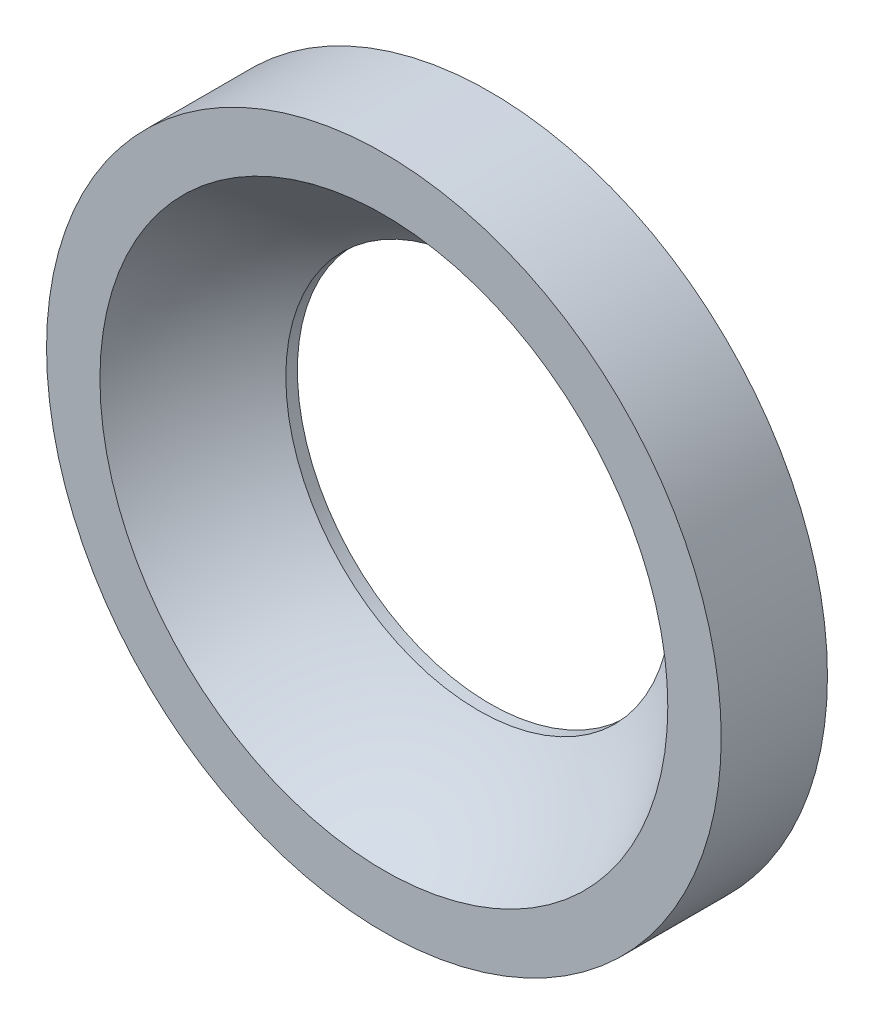
SolidWorks part; units mm, degrees
ref_plane "Front Plane" through (0, 0, 0) normal (0, 0, 1) x (1, 0, 0)
ref_plane "Top Plane" through (0, 0, 0) normal (0, 1, 0) x (1, 0, 0)
ref_plane "Right Plane" through (0, 0, 0) normal (1, 0, 0) x (0, 0, -1)
sketch "Sketch2" plane through (0, 0, 0) normal (0, 0, 1) x (1, 0, 0)
  circle A0 centre (0, 0) radius 22.225
  dimension "D1" = 44.45
extrude "Boss-Extrude1" add sketch "Sketch2" along normal blind 7
sketch "Sketch3" plane through (0, 0, 7) normal (0, 0, 1) x (1, 0, 0)
  circle A0 centre (0, 0) radius 12.7
  dimension "D1" = 25.4
extrude "Cut-Extrude1" cut sketch "Sketch3" against normal through all
sketch "Sketch4" plane through (0, 0, 0) normal (0, 1, 0) x (1, 0, 0)
  line L0 (0, 16.7642) -> (0, -16.7642) construction
  line L1 (-18.707, -7) -> (0, -7)
  line L2 (-22.8388, 0) -> (22.8388, 0) construction
  line L5 (0, -7) -> (0, -0.761)
  line L6 (0, -0.761) -> (-12.7, -0.761)
  arc A0 (-18.707, -7) -> (-12.7, -0.761) centre (0, -19) cw
  point P4 (0, 0)
  point P8 (0, 0)
  dimension "D1" = 22.225
  dimension "D2" = 7
  dimension "D3" = 19
  dimension "D4" = 12.7
revolve "Cut-Revolve1" cut sketch "Sketch4" angle 360 about L0
